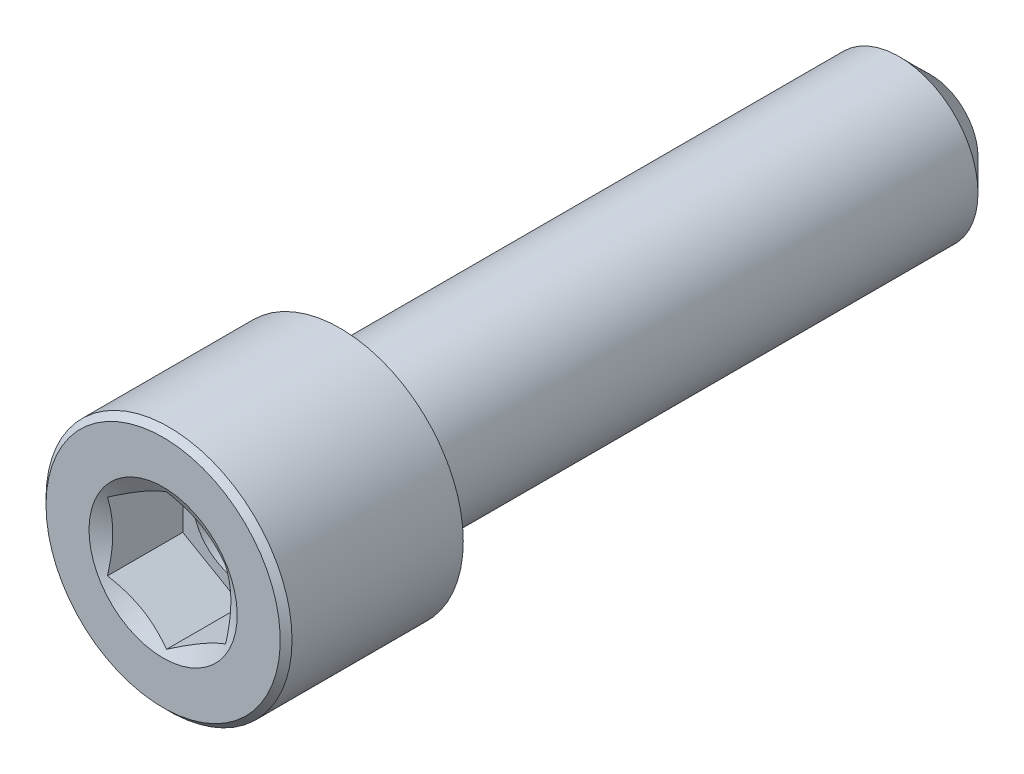
SolidWorks part; units mm, degrees
ref_plane "Спереди" through (0, 0, 0) normal (0, 0, 1) x (1, 0, 0)
ref_plane "Сверху" through (0, 0, 0) normal (0, 1, 0) x (1, 0, 0)
ref_plane "Справа" through (0, 0, 0) normal (1, 0, 0) x (0, 0, -1)
other "Configuration Table"
sketch "Эскиз1" plane through (0, 0, 0) normal (1, 0, 0) x (0, 0, -1)
  line L0 (-17.2074, 0) -> (21.7926, 0) construction
  line L1 (21.7926, 0) -> (21.7926, 4)
  line L2 (21.7926, 4) -> (-8.2074, 4)
  line L3 (-8.2074, 4) -> (-8.2074, 6.25)
  line L4 (-8.2074, 6.25) -> (-17.2074, 6.25)
  line L5 (-17.2074, 6.25) -> (-17.2074, 0)
  line L6 (-17.2074, 0) -> (21.7926, 0)
  dimension "D1" = 12.5
  dimension "D2" = 8
  dimension "D3" = 9
  dimension "D4" = 17.2074
  dimension "D5" = 39
revolve "Повернуть1" add sketch "Эскиз1" angle 360 about L0
cosmetic thread "Условное изображение резьбы1" parameters "D1"=22, "D2"=4.8
chamfer "Фаска1" distance 1.6 angle 45 1 edges at (4, 0, -21.7926)
chamfer "Фаска2" distance 0.3 angle 45 1 edges at (6.25, 0, 17.2074)
fillet "Скругление1" radius 0.5 1 edges at (4, 0, 8.2074)
sketch "Эскиз3" plane through (0, 0, 17.2074) normal (0, 0, 1) x (1, 0, 0)
  line L1 (0, 3.4641) -> (-3, 1.7321)
  line L2 (-3, 1.7321) -> (-3, -1.7321)
  line L3 (-3, -1.7321) -> (0, -3.4641)
  line L4 (0, -3.4641) -> (3, -1.7321)
  line L5 (3, -1.7321) -> (3, 1.7321)
  line L6 (3, 1.7321) -> (0, 3.4641)
  circle A0 centre (0, 0) radius 3 construction
  dimension "D1" = 6
extrude "Вырез-Вытянуть1" cut sketch "Эскиз3" against normal blind 4
sketch "Эскиз4" plane through (0, 0, 0) normal (1, 0, 0) x (0, 0, -1)
  line L2 (-17.2074, 5.95) -> (-17.2074, -5.95) construction
  line L9 (-17.2074, 0) -> (-13.0331, 0) construction
  line L10 (-17.2074, 1.7321) -> (-17.2074, -1.7321) construction
  line L11 (-17.2074, 3.7641) -> (-17.2074, 1.7321)
  line L13 (-13.2074, 1.7321) -> (-17.2074, 1.7321) construction
  line L14 (-16.0342, 1.7321) -> (-17.2074, 1.7321)
  line L15 (-17.2074, 3.7641) -> (-16.0342, 1.7321)
  dimension "D1" = 16.0342
  dimension "D2" = 3.7641
revolve "Вырез-Повернуть2" cut sketch "Эскиз4" angle 360 about L9
sketch "Эскиз6" plane through (0, 0, 0) normal (1, 0, 0) x (0, 0, -1)
  line L0 (0, 0) -> (-15.6727, 0) construction
  line L1 (-13.2074, 0) -> (-13.2074, 2.5)
  line L2 (-13.2074, 1.7321) -> (-13.2074, -1.7321) construction
  line L3 (-13.2074, 2.5) -> (-12.2074, 2.5)
  line L6 (-13.2074, 0) -> (-9.7074, 0)
  line L7 (-12.2074, 2.5) -> (-9.7074, 0)
  dimension "D1" = 9.7074
  dimension "D2" = 12.2074
  dimension "D3" = 2.5
revolve "Вырез-Повернуть3" cut sketch "Эскиз6" angle 360 about L0
